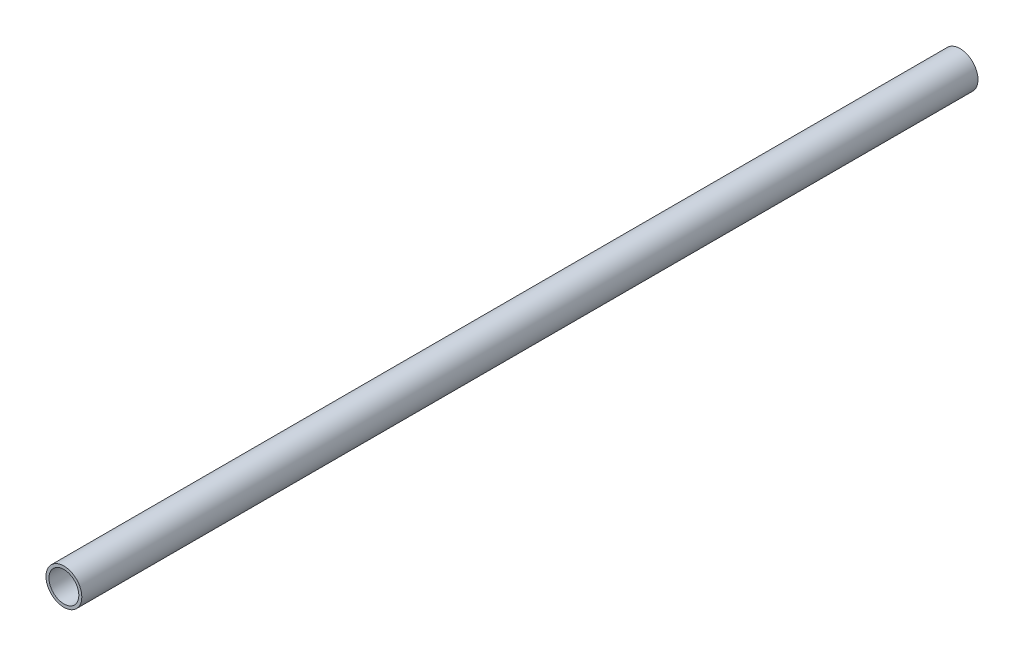
SolidWorks part; units mm, degrees
ref_plane "Front Plane" through (0, 0, 0) normal (0, 0, 1) x (1, 0, 0)
ref_plane "Top Plane" through (0, 0, 0) normal (0, 1, 0) x (1, 0, 0)
ref_plane "Right Plane" through (0, 0, 0) normal (1, 0, 0) x (0, 0, -1)
sketch "Sketch1" plane through (0, 0, 0) normal (0, 0, 1) x (1, 0, 0)
  circle A0 centre (0, 0) radius 6
  circle A1 centre (0, 0) radius 5
  dimension "D1" = 12
  dimension "D2" = 10
extrude "Boss-Extrude1" add sketch "Sketch1" along normal blind 300
